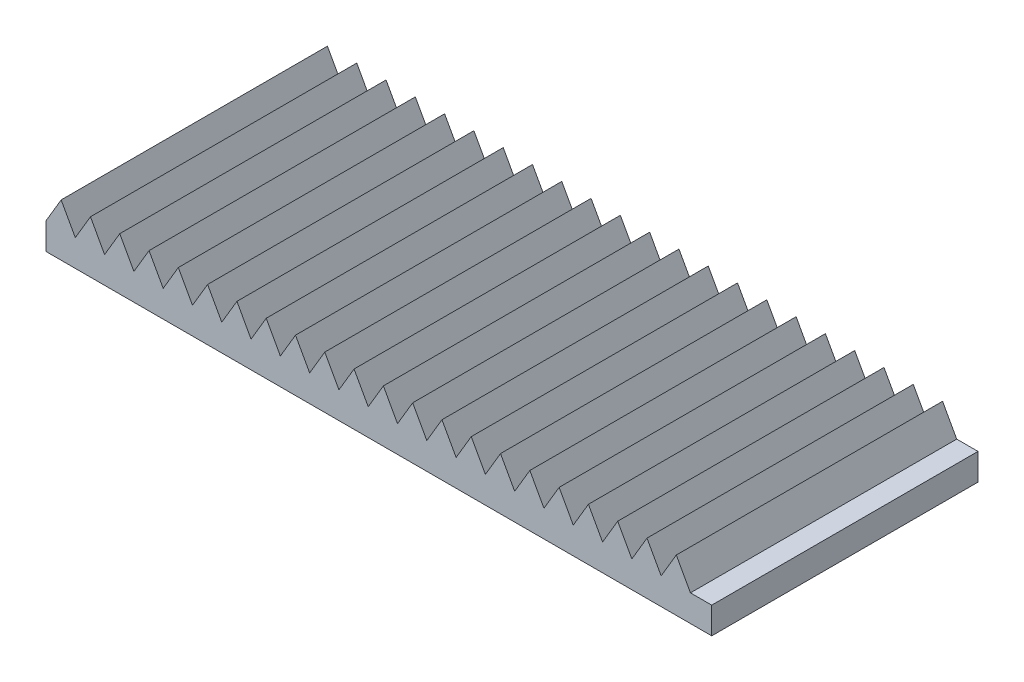
SolidWorks part; units mm, degrees
ref_plane "Front Plane" through (0, 0, 0) normal (0, 0, 1) x (1, 0, 0)
ref_plane "Top Plane" through (0, 0, 0) normal (0, 1, 0) x (1, 0, 0)
ref_plane "Right Plane" through (0, 0, 0) normal (1, 0, 0) x (0, 0, -1)
sketch "Sketch1" plane through (0, 0, 0) normal (0, 0, 1) x (1, 0, 0)
  line L0 (-14.2322, -0.4045) -> (-13.6626, 0.5602)
  line L2 (-14.2322, -0.4045) -> (-14.2322, -1.4045)
  line L3 (-14.2322, -1.4045) -> (10.7678, -1.4045)
  line L4 (10.7678, -0.4045) -> (10.7678, -1.4045)
  line L5 (-13.6626, 0.5602) -> (-13.1313, -0.403)
  line L6 (-13.1313, -0.403) -> (-12.5626, 0.5602)
  line L7 (-12.5626, 0.5602) -> (-12.0313, -0.403)
  line L8 (-12.0313, -0.403) -> (-11.4626, 0.5602)
  line L9 (-11.4626, 0.5602) -> (-10.9313, -0.403)
  line L10 (-10.9313, -0.403) -> (-10.3626, 0.5602)
  line L11 (-10.3626, 0.5602) -> (-9.8313, -0.403)
  line L12 (-9.8313, -0.403) -> (-9.2626, 0.5602)
  line L13 (-9.2626, 0.5602) -> (-8.7313, -0.403)
  line L14 (-8.7313, -0.403) -> (-8.1626, 0.5602)
  line L15 (-8.1626, 0.5602) -> (-7.6313, -0.403)
  line L16 (-7.6313, -0.403) -> (-7.0626, 0.5602)
  line L17 (-7.0626, 0.5602) -> (-6.5313, -0.403)
  line L18 (-6.5313, -0.403) -> (-5.9626, 0.5602)
  line L19 (-5.9626, 0.5602) -> (-5.4313, -0.403)
  line L20 (-5.4313, -0.403) -> (-4.8626, 0.5602)
  line L21 (-4.8626, 0.5602) -> (-4.3313, -0.403)
  line L22 (-4.3313, -0.403) -> (-3.7626, 0.5602)
  line L23 (-3.7626, 0.5602) -> (-3.2313, -0.403)
  line L24 (-3.2313, -0.403) -> (-2.6626, 0.5602)
  line L25 (-2.6626, 0.5602) -> (-2.1313, -0.403)
  line L26 (-2.1313, -0.403) -> (-1.5626, 0.5602)
  line L27 (-1.5626, 0.5602) -> (-1.0313, -0.403)
  line L28 (-1.0313, -0.403) -> (-0.4626, 0.5602)
  line L29 (-0.4626, 0.5602) -> (0.0687, -0.403)
  line L30 (0.0687, -0.403) -> (0.6374, 0.5602)
  line L31 (0.6374, 0.5602) -> (1.1687, -0.403)
  line L32 (1.1687, -0.403) -> (1.7374, 0.5602)
  line L33 (1.7374, 0.5602) -> (2.2687, -0.403)
  line L34 (2.2687, -0.403) -> (2.8374, 0.5602)
  line L35 (2.8374, 0.5602) -> (3.3687, -0.403)
  line L36 (3.3687, -0.403) -> (3.9374, 0.5602)
  line L37 (3.9374, 0.5602) -> (4.4687, -0.403)
  line L38 (4.4687, -0.403) -> (5.0374, 0.5602)
  line L39 (5.0374, 0.5602) -> (5.5687, -0.403)
  line L40 (5.5687, -0.403) -> (6.1374, 0.5602)
  line L41 (6.1374, 0.5602) -> (6.6687, -0.403)
  line L42 (6.6687, -0.403) -> (7.2374, 0.5602)
  line L43 (7.2374, 0.5602) -> (7.7687, -0.403)
  line L44 (7.7687, -0.403) -> (8.3374, 0.5602)
  line L45 (8.3374, 0.5602) -> (8.8687, -0.403)
  line L46 (8.8687, -0.403) -> (9.4374, 0.5602)
  line L47 (9.4374, 0.5602) -> (9.9695, -0.4045)
  line L68 (9.9695, -0.4045) -> (10.7678, -0.4045)
  dimension "D1" = 25
  dimension "D2" = 1
  dimension "D3" = 22
extrude "Boss-Extrude2" add sketch "Sketch1" along normal blind 10
